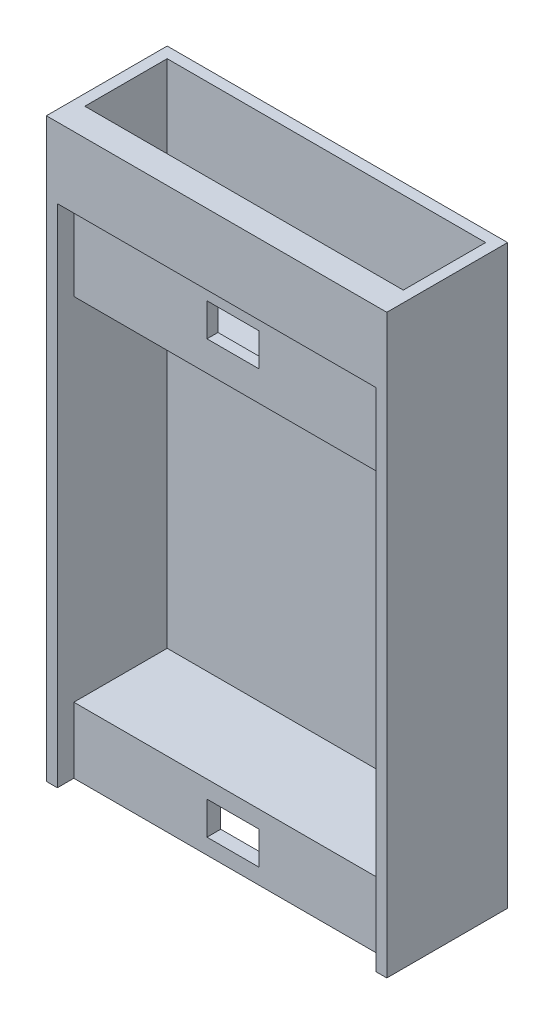
SolidWorks part; units mm, degrees
ref_plane "Front Plane" through (0, 0, 0) normal (0, 0, 1) x (1, 0, 0)
ref_plane "Top Plane" through (0, 0, 0) normal (0, 1, 0) x (1, 0, 0)
ref_plane "Right Plane" through (0, 0, 0) normal (1, 0, 0) x (0, 0, -1)
sketch "Sketch1" plane through (0, 0, 0) normal (0, 0, 1) x (1, 0, 0)
  line L1 (-31, 39) -> (31, 39)
  line L2 (-31, 39) -> (-31, -39)
  line L3 (-31, -39) -> (31, -39)
  line L4 (31, 39) -> (31, -39)
  point P4 (0, 39)
  point P6 (-31, 0)
  dimension "D1" = 62
  dimension "D2" = 78
extrude "Boss-Extrude1" add sketch "Sketch1" against normal blind 2
sketch "Sketch2" plane through (0, 0, 0) normal (0, 0, 1) x (1, 0, 0)
  line L1 (-31, 39) -> (31, 39)
  line L2 (-31, 39) -> (-31, -39)
  line L3 (-31, -39) -> (31, -39)
  line L4 (31, 39) -> (31, -39)
  line L5 (29, -27) -> (-29, -27)
  line L6 (29, -27) -> (29, 37)
  line L7 (29, 37) -> (-29, 37)
  line L8 (-29, -27) -> (-29, 37)
  dimension "D1" = 2
  dimension "D2" = 2
  dimension "D3" = 12
  dimension "D4" = 2
extrude "Boss-Extrude2" add sketch "Sketch2" along normal blind 20
sketch "Sketch3" plane through (0, 37, 0) normal (0, -1, 0) x (1, 0, 0)
  circle A0 centre (-20.4882, 8.7676) radius 3.3131
extrude "Cut-Extrude1" cut sketch "Sketch3" against normal up to next
sketch "Sketch4" plane through (0, 0, 0) normal (0, 0, 1) x (1, 0, 0)
  line L0 (31, -39) -> (31, 39) construction
  line L2 (-31, 39) -> (-31, 66)
  line L3 (-31, 66) -> (31, 66)
  line L4 (31, 39) -> (31, 66)
  line L10 (-31, 39) -> (31, 39)
  dimension "D1" = 27
extrude "Boss-Extrude3" add sketch "Sketch4" against normal blind 2
sketch "Sketch5" plane through (0, 0, 0) normal (0, 0, 1) x (1, 0, 0)
  line L0 (-31, 39) -> (-31, 66)
  line L2 (31, 66) -> (31, 39)
  line L3 (31, 39) -> (29, 39)
  line L4 (-31, 39) -> (31, 39) construction
  line L5 (29, 39) -> (29, 66)
  line L7 (-29, 66) -> (-29, 39)
  line L8 (-29, 39) -> (-31, 39)
  line L9 (31, 66) -> (-31, 66) construction
  line L11 (31, 66) -> (29, 66)
  line L12 (-29, 66) -> (-31, 66)
  dimension "D1" = 2
  dimension "D2" = 2
extrude "Boss-Extrude4" add sketch "Sketch5" along normal blind 20
sketch "Sketch6" plane through (0, 0, 20) normal (0, 0, 1) x (1, 0, 0)
  line L1 (-29, 66) -> (29, 66)
  line L2 (-29, 66) -> (-29, 39)
  line L3 (-29, 39) -> (29, 39)
  line L4 (29, 66) -> (29, 39)
  line L5 (-29, 39) -> (-29, 66) construction
  line L6 (29, 66) -> (-29, 66) construction
  point P6 (-27.8642, 55.314)
extrude "Boss-Extrude5" add sketch "Sketch6" against normal blind 2
sketch "Sketch9" plane through (0, 0, 0) normal (0, 0, 1) x (1, 0, 0)
  line L0 (-31, -39) -> (31, -39) construction
  line L1 (28.8739, -29) -> (-29, -29)
  line L2 (28.8739, -29) -> (28.8739, -39)
  line L3 (28.8739, -39) -> (-29, -39)
  line L4 (-29, -29) -> (-29, -39)
  line L5 (-29, 37) -> (-29, -27) construction
  line L6 (-29, -27) -> (29, -27) construction
  dimension "D1" = 2
extrude "Cut-Extrude4" cut sketch "Sketch9" along normal blind 14.5
sketch "Sketch12" plane through (0, 0, 18) normal (0, 0, -1) x (-1, 0, 0)
  line L1 (-29, 66) -> (29, 66)
  line L2 (-29, 66) -> (-29, 39)
  line L3 (-29, 39) -> (29, 39)
  line L4 (29, 66) -> (29, 39)
extrude "Boss-Extrude6" add sketch "Sketch12" along normal blind 3
sketch "Sketch13" plane through (0, 0, 20) normal (0, 0, 1) x (1, 0, 0)
  line L0 (-31, -39) -> (31, -39) construction
  line L1 (-29, 53.1439) -> (29, 53.1439)
  line L2 (-29, 53.1439) -> (-29, -39)
  line L3 (-29, -39) -> (29, -39)
  line L4 (29, 53.1439) -> (29, -39)
  line L5 (31, -39) -> (31, 66) construction
  line L6 (-31, 66) -> (-31, -39) construction
  dimension "D1" = 2
  dimension "D2" = 2
  dimension "D3" = 92.1439
extrude "Cut-Extrude6" cut sketch "Sketch13" against normal blind 3
sketch "Sketch14" plane through (0, 0, 17) normal (0, 0, 1) x (1, 0, 0)
  line L1 (-4.75, 48.4392) -> (4.75, 48.4392)
  line L2 (-4.75, 48.4392) -> (-4.75, 42.4392)
  line L3 (-4.75, 42.4392) -> (4.75, 42.4392)
  line L4 (4.75, 48.4392) -> (4.75, 42.4392)
  line L5 (-4.75, -30.1608) -> (4.75, -30.1608)
  line L6 (-4.75, -30.1608) -> (-4.75, -36.1608)
  line L7 (-4.75, -36.1608) -> (4.75, -36.1608)
  line L8 (4.75, -30.1608) -> (4.75, -36.1608)
  line L9 (29, 53.1439) -> (-29, 53.1439) construction
  point P8 (0, 48.4392)
  point P10 (0, -30.1608)
  point P11 (4.75, -33.1608)
  point P14 (4.75, 45.4392)
  dimension "D1" = 9.5
  dimension "D2" = 6
  dimension "D3" = 78.6
extrude "Cut-Extrude7" cut sketch "Sketch14" against normal up to surface (17 mm away) up to face at (-0.0631, -34, 0)
equation "\"batteries_width\"=55"
equation "\"padding\"=1.5"
equation "\"D1@Sketch1\"=\"padding\"*2+\"batteries_width\"+\"wall\"*2"
equation "\"batteries_height\"=61"
equation "\"D2@Sketch1\"=\"batteries_height\"+\"padding\"*2+\"wall\"*2+10"
equation "\"wall\"=2"
equation "\"D1@Boss-Extrude1\"=\"wall\""
equation "\"D1@Sketch2\"=\"wall\""
equation "\"D2@Sketch2\"=\"wall\""
equation "\"D3@Sketch2\"=\"wall\"+10"
equation "\"D4@Sketch2\"=\"wall\""
equation "\"D1@Sketch4\"=25+\"wall\""
equation "\"D1@Boss-Extrude3\"=\"wall\""
equation "\"D1@Sketch5\"=\"wall\""
equation "\"D2@Sketch5\"=\"wall\""
equation "\"D1@Sketch9\"=\"wall\""
equation "\"D1@Sketch13\"=\"wall\""
equation "\"D2@Sketch13\"=\"wall\""
